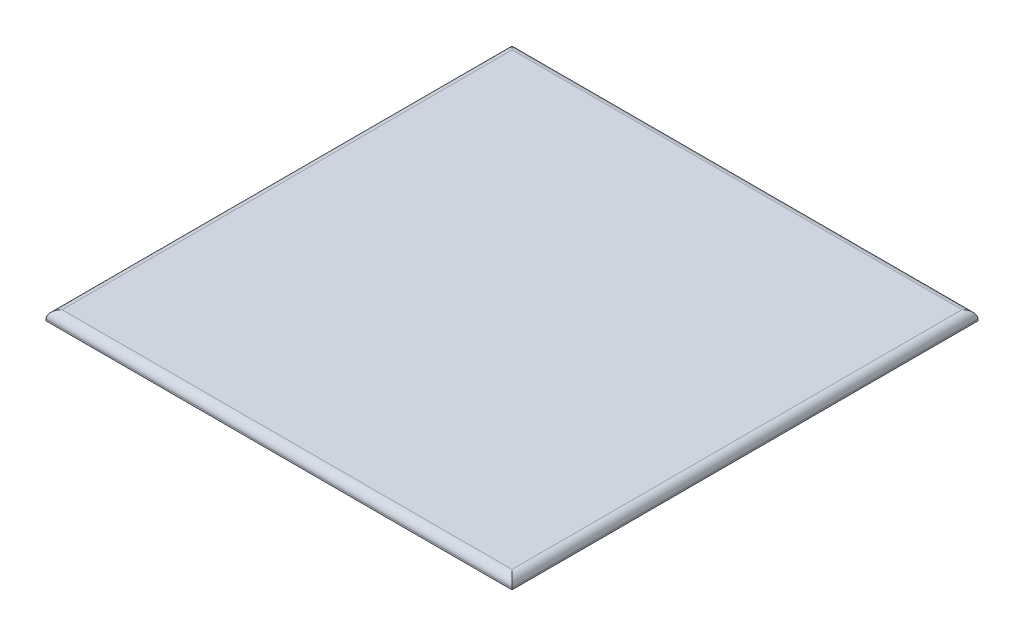
SolidWorks part; units mm, degrees
ref_plane "Front Plane" through (0, 0, 0) normal (0, 0, 1) x (1, 0, 0)
ref_plane "Top Plane" through (0, 0, 0) normal (0, 1, 0) x (1, 0, 0)
ref_plane "Right Plane" through (0, 0, 0) normal (1, 0, 0) x (0, 0, -1)
sketch "Sketch1" plane through (0, 0, 0) normal (0, 1, 0) x (1, 0, 0)
  line L1 (0, 0) -> (145, 0)
  line L2 (0, 0) -> (0, 145)
  line L3 (0, 145) -> (145, 145)
  line L4 (145, 0) -> (145, 145)
  dimension "D1" = 145
  dimension "D2" = 145
extrude "Boss-Extrude1" add sketch "Sketch1" along normal blind 3
fillet "Fillet1" radius 2.5 4 edges at (145, 3, -72.5) (72.5, 3, -145) (0, 3, -72.5) (72.5, 3, 0)
sketch "Sketch2" plane through (0, 0, 0) normal (0, -1, 0) x (1, 0, 0)
  line L0 (60, 0) -> (60, -145) construction
  line L1 (0, 0) -> (145, 0) construction
  line L2 (145, -145) -> (0, -145) construction
  line L3 (0, -145) -> (0, 0) construction
  line L4 (85, 0) -> (85, -145) construction
  line L5 (145, 0) -> (145, -145) construction
  line L6 (60, -30) -> (85, -30) construction
  line L8 (60, -30) -> (85, -30)
  line L9 (60, -30) -> (60, -45)
  line L10 (60, -45) -> (85, -45)
  line L11 (85, -30) -> (85, -45)
  dimension "D1" = 60
  dimension "D2" = 60
  dimension "D3" = 30
  dimension "D4" = 15
extrude "Cut-Extrude1" cut sketch "Sketch2" against normal blind 1
